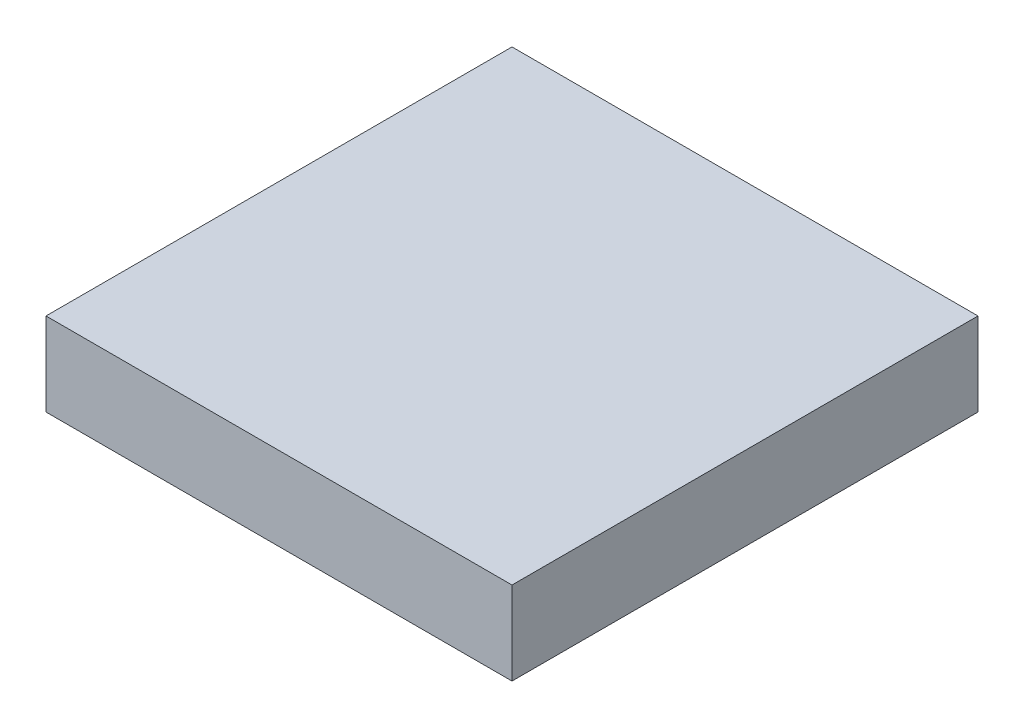
SolidWorks part; units mm, degrees
ref_plane "Front Plane" through (0, 0, 0) normal (0, 0, 1) x (1, 0, 0)
ref_plane "Top Plane" through (0, 0, 0) normal (0, 1, 0) x (1, 0, 0)
ref_plane "Right Plane" through (0, 0, 0) normal (1, 0, 0) x (0, 0, -1)
sketch "Sketch1" plane through (0, 0, 0) normal (0, 1, 0) x (1, 0, 0)
  line L1 (355.6, 355.6) -> (-355.6, 355.6)
  line L2 (355.6, 355.6) -> (355.6, -355.6)
  line L3 (355.6, -355.6) -> (-355.6, -355.6)
  line L4 (-355.6, 355.6) -> (-355.6, -355.6)
  line L5 (355.6, 355.6) -> (-355.6, -355.6) construction
  line L6 (355.6, -355.6) -> (-355.6, 355.6) construction
  point P0 (0, 0)
  dimension "D1" = 711.2
  dimension "D2" = 711.2
extrude "Boss-Extrude1" add sketch "Sketch1" along normal blind 127
